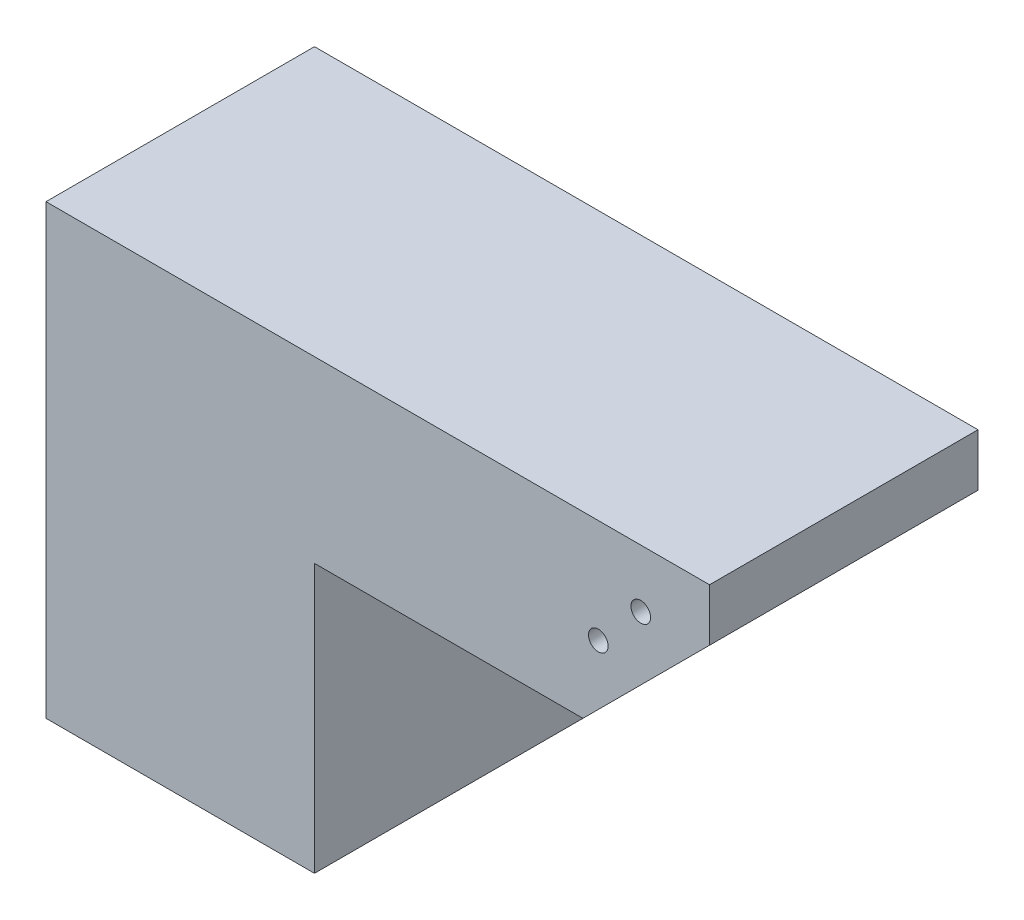
SolidWorks part; units mm, degrees
ref_plane "Front Plane" through (0, 0, 0) normal (0, 0, 1) x (1, 0, 0)
ref_plane "Top Plane" through (0, 0, 0) normal (0, 1, 0) x (1, 0, 0)
ref_plane "Right Plane" through (0, 0, 0) normal (1, 0, 0) x (0, 0, -1)
sketch "Sketch1" plane through (0, 0, 0) normal (0, 0, 1) x (1, 0, 0)
  line L0 (0, 0) -> (15, 0)
  line L1 (15, 0) -> (15, 30)
  line L2 (15, 30) -> (45, 30)
  line L3 (45, 30) -> (59.1421, 44.1421)
  line L4 (59.1421, 44.1421) -> (59.1421, 50)
  line L5 (59.1421, 50) -> (-15, 50)
  line L6 (-15, 50) -> (-15, 0)
  line L7 (-15, 0) -> (0, 0)
  dimension "D3" = 30
  dimension "D1" = 30
  dimension "D2" = 15
  dimension "D4" = 45
  dimension "D5" = 50
  dimension "D6" = 135
  dimension "D7" = 20
extrude "Boss-Extrude1" add sketch "Sketch1" along normal mid plane 30
sketch "Sketch2" plane through (0, 0, 0) normal (0, -1, 0) x (1, 0, 0)
  line L1 (-11.85, 11.85) -> (11.85, 11.85)
  line L2 (-11.85, 11.85) -> (-11.85, -11.85)
  line L3 (-11.85, -11.85) -> (11.85, -11.85)
  line L4 (11.85, 11.85) -> (11.85, -11.85)
  line L5 (-11.85, 11.85) -> (11.85, -11.85) construction
  line L6 (-11.85, -11.85) -> (11.85, 11.85) construction
  point P0 (0, 0)
  dimension "D1" = 23.7
  dimension "D2" = 23.7
extrude "Cut-Extrude1" cut sketch "Sketch2" against normal blind 26
sketch "Sketch5" plane through (7.5, -7.5, 0) normal (0.7071, -0.7071, 0) x (0, 0, -1)
  line L0 (-15, 73.033) -> (15, 53.033) construction
  line L1 (15, 73.033) -> (-15, 53.033) construction
  line L3 (-6.1, 69.133) -> (6.1, 69.133)
  line L4 (-6.1, 69.133) -> (-6.1, 56.933)
  line L5 (-6.1, 56.933) -> (6.1, 56.933)
  line L6 (6.1, 69.133) -> (6.1, 56.933)
  line L7 (-6.1, 69.133) -> (6.1, 56.933) construction
  line L8 (-6.1, 56.933) -> (6.1, 69.133) construction
  point P8 (0, 63.033)
  dimension "D1" = 12.2
  dimension "D2" = 12.2
extrude "Cut-Extrude3" cut sketch "Sketch5" against normal blind 10.4
sketch "Sketch6" plane through (0, 0, 15) normal (0, 0, 1) x (1, 0, 0)
  line L0 (-15, 0) -> (15, 0) construction
  circle A0 centre (51.46, 43.54) radius 1.1
  point P4 (0, 0)
  dimension "D1" = 2.2
  dimension "D2" = 43.54
  dimension "D3" = 51.46
extrude "Cut-Extrude4" cut sketch "Sketch6" against normal through all
sketch "Sketch7" plane through (0, 0, 15) normal (0, 0, 1) x (1, 0, 0)
  circle A0 centre (46.7144, 38.3942) radius 1.1
  circle A1 centre (51.46, 43.54) radius 1.1 construction
  circle A2 centre (51.46, 43.54) radius 1.1 construction
  dimension "D1" = 2.2
  dimension "D2" = 7
  dimension "D3" = 4.7456
extrude "Cut-Extrude5" cut sketch "Sketch7" against normal through all
equation "\"board_w\"= 33.8"
equation "\"board_l\"= 41"
equation "\"stack_h\"= 19.5"
equation "\"module_w\"= 9.9"
equation "\"lens_d\"= 7.8"
equation "\"lens_from_end\"= 8"
equation "\"usb_w\"= 13"
equation "\"plug_h\"= 7"
equation "\"usb_from_back\"= 6"
equation "\"clear\"= 0.4"
equation "\"wall\"= 3"
equation "\"floor_t\"= 2.5"
equation "\"pocket_clear\"= 0.3"
equation "\"lens_clear\"= 0.6"
equation "\"plate_w\"= 16"
equation "\"plate_clear\"= 0.3"
equation "\"plate_t\"= 1.2"
equation "\"plate_seat\"= 0.8"
equation "\"window_d\"= 12"
equation "\"lid_t\"= 2"
equation "\"lid_gap\"= 1"
equation "\"groove_d\"= 1.2"
equation "\"groove_clear\"= 0.15"
equation "\"lip_top\"= 1.2"
equation "\"side_clear\"= 0.2"
equation "\"slide_clear\"= 0.2"
equation "\"ball_d\"= 16"
equation "\"ball_clear\"= 0.3"
equation "\"lip\"= 1.2"
equation "\"cup_floor\"= 1.2"
equation "\"cup_d\"= 26"
equation "\"slit_w\"= 1.5"
equation "\"slit_depth\"= 9"
equation "\"lug_w\"= 16"
equation "\"m3_hole\"= 3.4"
equation "\"m3_nut\"= 5.7"
equation "\"m3_nut_d\"= 2.6"
equation "\"boss_d\"= 20"
equation "\"boss_h\"= 8"
equation "\"nut_af\"= 11.4"
equation "\"nut_t\"= 5.8"
equation "\"screw_hole\"= 6.6"
equation "\"post_w\"= 30"
equation "\"post_len\"= 120"
equation "\"spigot_w\"= 23.7"
equation "\"bore_w\"= 24"
equation "\"spigot_len\"= 25"
equation "\"base_w\"= 130"
equation "\"base_h\"= 40"
equation "\"hole_depth\"= 30"
equation "\"base_clear\"= 0.4"
equation "\"base_col\"= 42"
equation "\"base_shell\"= 3"
equation "\"head_h\"= 50"
equation "\"arm_under\"= 30"
equation "\"arm_reach\"= 45"
equation "\"face_run\"= 20"
equation "\"bb_d\"= 24"
equation "\"bb_h\"= 10"
equation "\"neck_d\"= 8"
equation "\"ball_drop\"= 14"
equation "\"in_l\"= \"board_l\" + 2 * \"clear\""
equation "\"in_w\"= \"board_w\" + 2 * \"clear\""
equation "\"out_l\"= \"in_l\" + 2 * \"wall\""
equation "\"out_w\"= \"in_w\" + 2 * \"wall\""
equation "\"y_groove\"= \"floor_t\" - \"plate_seat\" + \"stack_h\" + \"lid_gap\""
equation "\"groove_h\"= \"lid_t\" + 2 * \"groove_clear\""
equation "\"tray_h\"= \"y_groove\" + \"groove_h\" + \"lip_top\""
equation "\"lid_w\"= \"in_w\" + 2 * \"groove_d\" - 2 * \"side_clear\""
equation "\"lid_right\"= \"in_l\" / 2 + \"groove_d\" - \"slide_clear\""
equation "\"lid_left\"= \"out_l\" / 2"
equation "\"open_d\"= \"ball_d\" - 2 * \"lip\""
equation "\"c_ball\"= sqr( ( ( \"ball_d\" + \"ball_clear\" ) / 2 ) ^ 2 - ( \"open_d\" / 2 ) ^ 2 )"
equation "\"cup_h\"= \"cup_floor\" + ( \"ball_d\" + \"ball_clear\" ) / 2 + \"c_ball\""
equation "\"lug_in\"= \"cup_d\" / 2 - 5"
equation "\"lug_out\"= \"cup_d\" / 2 + 4"
equation "\"D3@Sketch1\"=\"arm_under\""
equation "\"D1@Sketch1\"=30"
equation "\"D4@Sketch1\"=\"arm_reach\""
equation "\"D5@Sketch1\"=\"head_h\""
equation "\"D6@Sketch1\"=180-45"
equation "\"D7@Sketch1\"=\"face_run\""
equation "\"D1@Boss-Extrude1\"=\"post_w\""
equation "\"D1@Cut-Extrude1\"=\"spigot_len\"+1"
equation "\"D1@Sketch5\"=12.2"
equation "\"D2@Sketch5\"=12.2"
